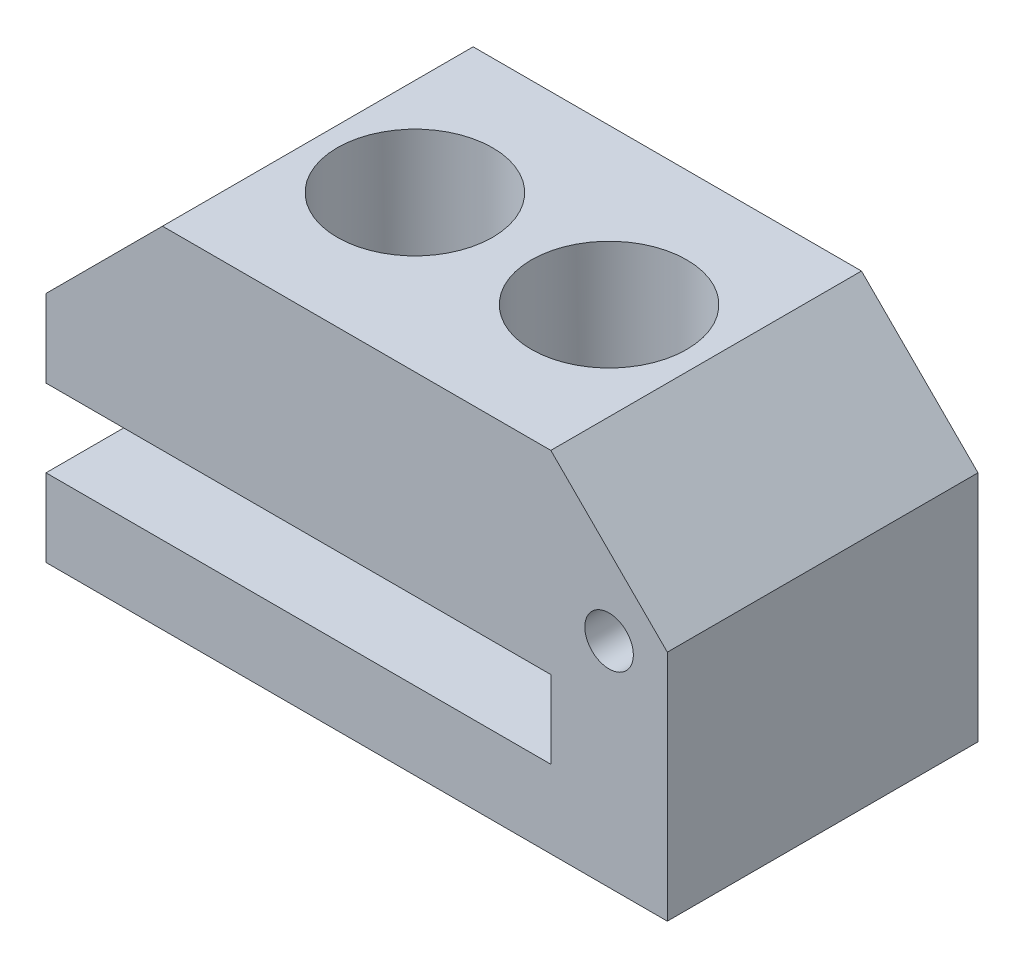
SolidWorks part; units mm, degrees
material "Brass"
ref_plane "Front Plane" through (0, 0, 0) normal (0, 0, 1) x (1, 0, 0)
ref_plane "Top Plane" through (0, 0, 0) normal (0, 1, 0) x (1, 0, 0)
ref_plane "Right Plane" through (0, 0, 0) normal (1, 0, 0) x (0, 0, -1)
sketch "Sketch1" plane through (0, 0, 0) normal (0, 0, 1) x (1, 0, 0)
  line L0 (0, 0) -> (32, 0)
  line L1 (32, 0) -> (32, 12)
  line L2 (32, 12) -> (26, 18)
  line L3 (26, 18) -> (6, 18)
  line L4 (6, 18) -> (0, 12)
  line L5 (0, 12) -> (0, 0)
extrude "Boss-Extrude1" add sketch "Sketch1" along normal blind 16
sketch "Sketch2" plane through (0, 0, 0) normal (0, 1, 0) x (1, 0, 0)
  circle A0 centre (11, -8) radius 4
  circle A1 centre (21, -8) radius 4
  dimension "D1" = 8
  dimension "D2" = 8
extrude "Cut-Extrude1" cut sketch "Sketch2" against normal mid plane 80
sketch "Sketch3" plane through (0, 0, 0) normal (0, 0, 1) x (1, 0, 0)
  line L0 (0, 4) -> (26, 4)
  line L1 (0, 12) -> (0, 0) construction
  line L2 (26, 4) -> (26, 8)
  line L3 (26, 8) -> (0, 8)
  line L4 (0, 8) -> (0, 4)
extrude "Cut-Extrude2" cut sketch "Sketch3" against normal mid plane 80
sketch "Sketch4" plane through (0, 0, 0) normal (0, 0, 1) x (1, 0, 0)
  circle A0 centre (29, 11) radius 1.25
  dimension "D1" = 2.5
extrude "Cut-Extrude3" cut sketch "Sketch4" against normal mid plane 80
